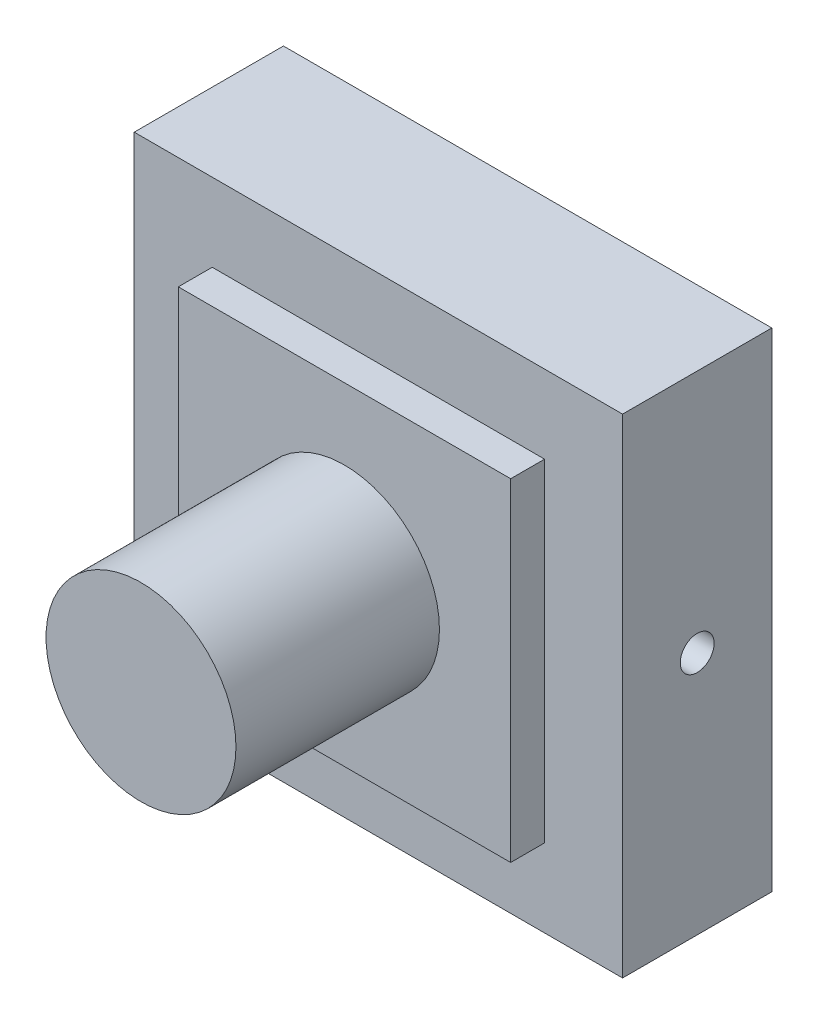
SolidWorks part; units mm, degrees
ref_plane "前视基准面" through (0, 0, 0) normal (0, 0, 1) x (1, 0, 0)
ref_plane "上视基准面" through (0, 0, 0) normal (0, 1, 0) x (1, 0, 0)
ref_plane "右视基准面" through (0, 0, 0) normal (1, 0, 0) x (0, 0, -1)
sketch "草图1" plane through (0, 0, 0) normal (0, 0, 1) x (1, 0, 0)
  line L1 (-18, -18) -> (18, -18)
  line L2 (-18, -18) -> (-18, 18)
  line L3 (-18, 18) -> (18, 18)
  line L4 (18, -18) -> (18, 18)
  line L5 (-18, -18) -> (18, 18) construction
  line L6 (-18, 18) -> (18, -18) construction
  point P0 (0, 0)
  dimension "D1" = 36
  dimension "D2" = 36
extrude "凸台-拉伸1" add sketch "草图1" along normal blind 11
sketch "草图2" plane through (0, 0, 11) normal (0, 0, 1) x (1, 0, 0)
  line L2 (-12.25, 12.25) -> (12.25, 12.25)
  line L3 (-12.25, 12.25) -> (-12.25, -12.25)
  line L4 (-12.25, -12.25) -> (12.25, -12.25)
  line L6 (12.25, 12.25) -> (12.25, -12.25)
  line L7 (-12.25, 12.25) -> (12.25, -12.25) construction
  line L8 (-12.25, -12.25) -> (12.25, 12.25) construction
  point P0 (0, 0)
  dimension "D1" = 24.5
  dimension "D2" = 24.5
extrude "凸台-拉伸2" add sketch "草图2" along normal blind 2.5
sketch "草图3" plane through (0, 0, 13.5) normal (0, 0, 1) x (1, 0, 0)
  circle A0 centre (0, 0) radius 7
  dimension "D1" = 14
extrude "凸台-拉伸3" add sketch "草图3" along normal blind 15
hole_wizard "Ø2.5 (2.5) 直径孔1" positions "草图5" profile "草图4" hole size "Ø2.5" standard "GB" end condition through all
sketch "草图5" plane through (18, 0, 0) normal (1, 0, 0) x (0, 0, -1)
  line L0 (-11, -12.25) -> (-11, 12.25) construction
  point P0 (-5.5, 0)
  dimension "D1" = 5.5
sketch "草图4" plane through (18, 0, 5.5) normal (0, 1, 0) x (0, 0, -1)
  line L0 (0, 0) -> (0, 36)
  line L1 (0, 36) -> (1.25, 36)
  line L2 (1.25, 36) -> (1.25, 0)
  line L5 (1.25, 0) -> (0, 0)
  line L11 (0, -6.35) -> (0, 107.95) construction
  dimension "通孔孔直径" = 2.5
  dimension "通孔孔深度" = 36
